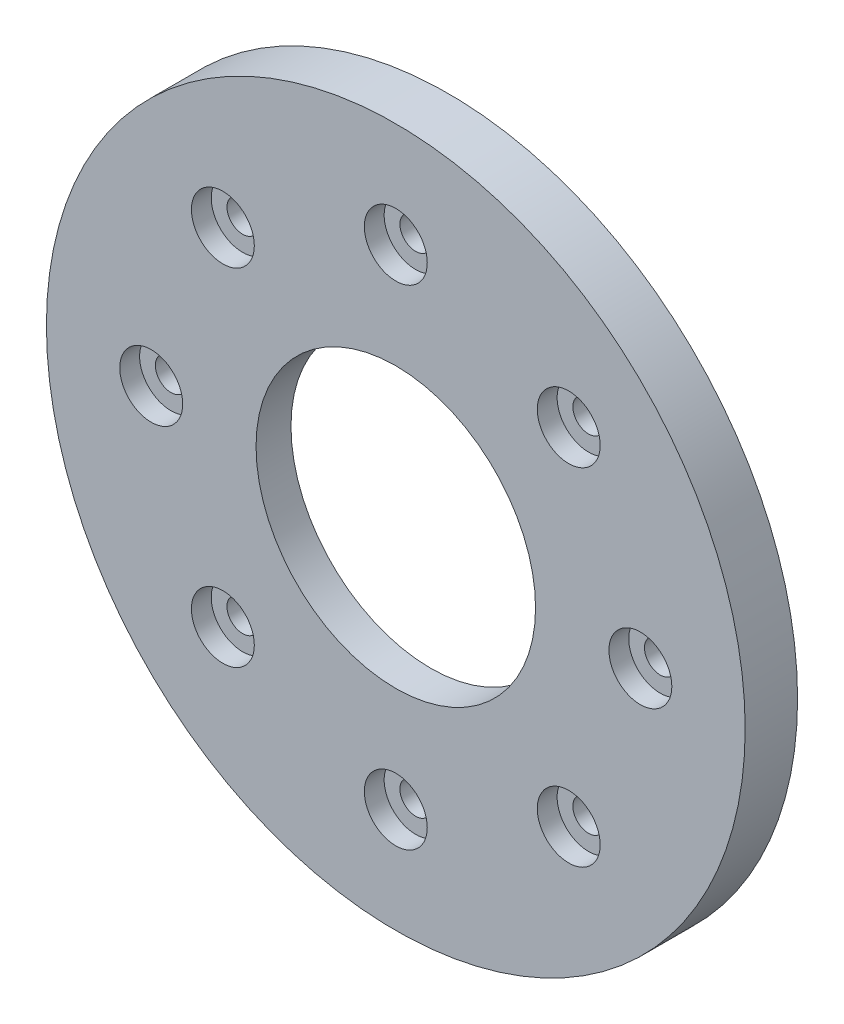
SolidWorks part; units mm, degrees
material "Plain Carbon Steel"
ref_plane "Front Plane" through (0, 0, 0) normal (0, 0, 1) x (1, 0, 0)
ref_plane "Top Plane" through (0, 0, 0) normal (0, 1, 0) x (1, 0, 0)
ref_plane "Right Plane" through (0, 0, 0) normal (1, 0, 0) x (0, 0, -1)
sketch "Sketch1" plane through (0, 0, 0) normal (0, 0, 1) x (1, 0, 0)
  circle A0 centre (0, 0) radius 100
  circle A1 centre (0, 0) radius 40
  circle A2 centre (0, 0) radius 70 construction
  circle A3 centre (0, 70) radius 4.25 construction
  dimension "D1" = 200
  dimension "D2" = 80
  dimension "D3" = 140
  dimension "D4" = 8.5
extrude "Boss-Extrude1" add sketch "Sketch1" along normal blind 15
hole_wizard "CBORE for M8 Hex Head Bolt1" positions "Sketch3" profile "Sketch4" counterbore size "M8" standard "ANSI Metric" end condition through all
sketch "Sketch3" plane through (0, 0, 15) normal (0, 0, 1) x (1, 0, 0)
  circle A0 centre (0, 0) radius 70 construction
  point P0 (0, 70)
  dimension "D1" = 140
sketch "Sketch4" plane through (0, 70, 15) normal (1, 0, 0) x (0, -1, 0)
  line L0 (0, 0) -> (0, 15)
  line L1 (0, 15) -> (4.5, 15)
  line L3 (4.5, 15) -> (4.5, 5.68)
  line L4 (4.5, 5.68) -> (9.005, 5.68)
  line L5 (9.005, 5.68) -> (9.005, 0)
  line L7 (9.005, 0) -> (0, 0)
  line L11 (0, -6.35) -> (0, 107.95) construction
  dimension "Thru Hole Dia." = 9
  dimension "Thru Hole Depth" = 15
  dimension "C'Bore Dia." = 18.01
  dimension "C'Bore Depth" = 5.68
pattern_circular "CirPattern1" count 8 over 360 about axis through (0, 0, 0) along (0, 0, 1) of "CBORE for M8 Hex Head Bolt1"
sketch "Sketch5" plane through (0, 0, 0) normal (0, 0, -1) x (-1, 0, 0)
  circle A0 centre (0, 0) radius 82.5
  dimension "D1" = 165
extrude "Cut-Extrude2" cut sketch "Sketch5" against normal blind 5
